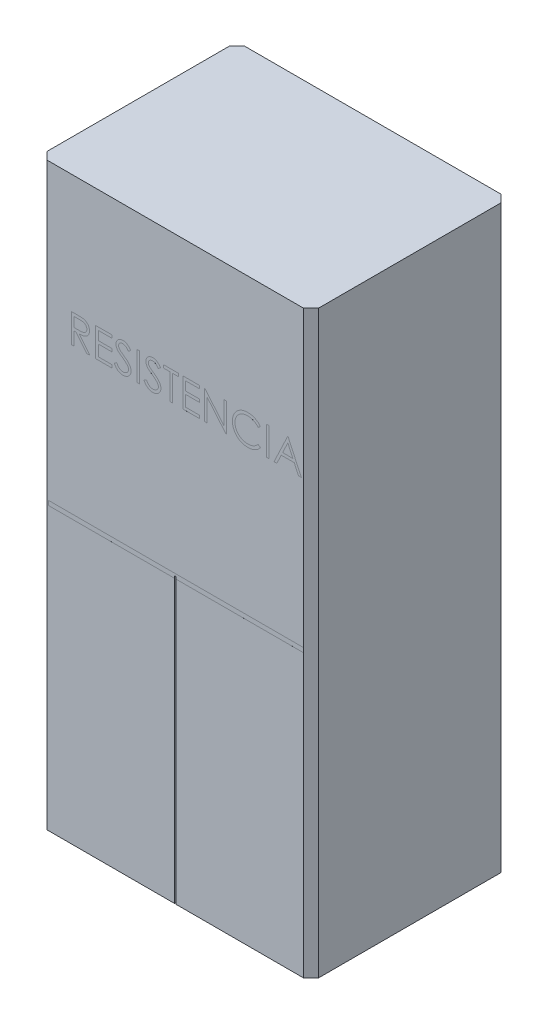
SolidWorks part; units mm, degrees
ref_plane "Alzado" through (0, 0, 0) normal (0, 0, 1) x (1, 0, 0)
ref_plane "Planta" through (0, 0, 0) normal (0, 1, 0) x (1, 0, 0)
ref_plane "Vista lateral" through (0, 0, 0) normal (1, 0, 0) x (0, 0, -1)
sketch "Croquis1" plane through (0, 0, 0) normal (0, 1, 0) x (1, 0, 0)
  line L0 (-550, 370) -> (-520, 400)
  line L1 (-520, 400) -> (520, 400)
  line L2 (-550, 370) -> (-550, -370)
  line L3 (-520, -400) -> (520, -400)
  line L4 (550, 370) -> (550, -370)
  line L5 (-550, 400) -> (550, -400) construction
  line L6 (-550, -400) -> (550, 400) construction
  line L7 (-550, -370) -> (-520, -400)
  line L8 (520, -400) -> (550, -370)
  line L9 (520, 400) -> (550, 370)
  point P0 (0, 0)
  dimension "D1" = 1100
  dimension "D2" = 800
extrude "Saliente-Extruir1" add sketch "Croquis1" along normal blind 1150
sketch "Croquis2" plane through (0, 0, 400) normal (0, 0, 1) x (1, 0, 0)
  line L0 (-520, 0) -> (520, 0) construction
  line L1 (-3.1217, 1150) -> (3.1479, 1150)
  line L2 (-3.1217, 1150) -> (-3.1217, 0)
  line L3 (-3.1217, 0) -> (3.1479, 0)
  line L4 (3.1479, 1150) -> (3.1479, 0)
  line L5 (-3.1217, 1150) -> (3.1479, 0) construction
  line L6 (-3.1217, 0) -> (3.1479, 1150) construction
  line L7 (-520, 1150) -> (520, 1150) construction
  point P0 (0.0131, 575)
extrude "Cortar-Extruir1" cut sketch "Croquis2" against normal blind 51
sketch "Croquis3" plane through (0, 1150, 0) normal (0, 1, 0) x (1, 0, 0)
  line L0 (-550, 370) -> (-520, 400)
  line L1 (-520, 400) -> (520, 400)
  line L2 (520, 400) -> (550, 370)
  line L3 (550, 370) -> (550, -370)
  line L4 (550, -370) -> (520, -400)
  line L5 (520, -400) -> (-520, -400)
  line L6 (-520, -400) -> (-550, -370)
  line L7 (-550, -370) -> (-550, 370)
extrude "Saliente-Extruir2" add sketch "Croquis3" along normal blind 1200
sketch "Croquis4" plane through (0, 0, 400) normal (0, 0, 1) x (1, 0, 0)
  line L0 (520, 2350) -> (520, 0) construction
  line L1 (-513.7043, 1159.0649) -> (520, 1159.0649)
  line L2 (-513.7043, 1159.0649) -> (-513.7043, 1140.9351)
  line L3 (-513.7043, 1140.9351) -> (520, 1140.9351)
  line L4 (520, 1159.0649) -> (520, 1140.9351)
  line L5 (-513.7043, 1159.0649) -> (520, 1140.9351) construction
  line L6 (-513.7043, 1140.9351) -> (520, 1159.0649) construction
  point P0 (3.1479, 1150)
extrude "Cortar-Extruir2" cut sketch "Croquis4" against normal blind 0.01
sketch "Croquis6" plane through (0, 0, 400) normal (0, 0, 1) x (1, 0, 0)
  line L0 (-435.6523, 1751.7442) -> (480.2076, 1751.7442) construction
  text T0 "RESISTENCIA" font "Century Gothic" height in points 440
extrude "Cortar-Extruir4" cut sketch "Croquis6" against normal blind 0.01
